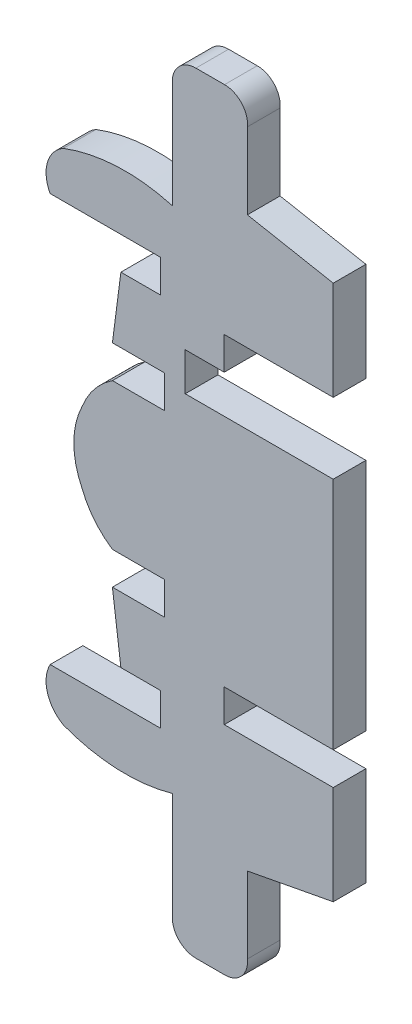
SolidWorks part; units mm, degrees
ref_plane "Front" through (0, 0, 0) normal (0, 0, 1) x (1, 0, 0)
ref_plane "Top" through (0, 0, 0) normal (0, 1, 0) x (1, 0, 0)
ref_plane "Right" through (0, 0, 0) normal (1, 0, 0) x (0, 0, -1)
sketch "Sketch1" plane through (0, 0, 0) normal (0, 0, 1) x (1, 0, 0)
  line L0 (796.0674, -94.7906) -> (796.0674, -97.7906)
  line L1 (801.5316, -91.996) -> (797.955, -91.996)
  line L2 (791.2726, -94.7906) -> (796.0674, -94.7906)
  line L3 (787.7336, -104.496) -> (811.5316, -104.496) construction
  line L4 (811.5316, -88.996) -> (811.5316, -79.92)
  line L5 (796.7638, -71.3014) -> (796.7638, -81.1469)
  line L6 (791.2726, -114.2013) -> (792.0513, -120.2055)
  line L7 (803.6575, -130.5631) -> (811.5316, -129.0719)
  line L8 (803.6575, -130.5631) -> (803.6575, -137.5522)
  line L9 (798.9334, -139.86) -> (801.5592, -139.86)
  line L10 (785.561, -123.2055) -> (795.6687, -123.2055)
  line L11 (792.0513, -120.2055) -> (795.6687, -120.2055)
  line L12 (795.6687, -120.2055) -> (795.6687, -123.2055)
  line L13 (801.5316, -88.996) -> (811.5316, -88.996)
  line L14 (797.955, -91.996) -> (797.955, -94.996)
  line L15 (796.0674, -97.7906) -> (791.2726, -97.7906)
  line L17 (796.0674, -111.2013) -> (791.2726, -111.2013)
  line L18 (801.5316, -91.996) -> (801.5316, -88.996)
  line L19 (796.7638, -137.6905) -> (796.7638, -127.8451)
  line L20 (811.5316, -119.996) -> (811.5316, -129.0719)
  line L21 (791.2726, -114.2013) -> (796.0674, -114.2013)
  line L22 (811.5316, -95.496) -> (811.5316, -116.996)
  line L23 (811.5316, -116.996) -> (801.5316, -116.996)
  line L24 (795.6687, -88.7864) -> (795.6687, -85.7864)
  line L25 (792.0513, -88.7864) -> (795.6687, -88.7864)
  line L26 (785.561, -85.7864) -> (795.6687, -85.7864)
  line L27 (798.9334, -69.1319) -> (801.5592, -69.1319)
  line L28 (803.6575, -78.4289) -> (803.6575, -71.4397)
  line L29 (796.0674, -114.2013) -> (796.0674, -111.2013)
  line L30 (803.6575, -78.4289) -> (811.5316, -79.92)
  line L31 (791.2726, -94.7906) -> (792.0513, -88.7864)
  line L32 (801.5316, -116.996) -> (801.5316, -119.996)
  line L33 (801.5316, -119.996) -> (811.5316, -119.996)
  line L34 (797.955, -94.996) -> (797.955, -95.496)
  line L35 (797.955, -95.496) -> (811.5316, -95.496)
  arc A0 (801.5592, -139.86) -> (803.6575, -137.5522) centre (801.5697, -137.7618) ccw
  arc A1 (796.7638, -137.6905) -> (798.9334, -139.86) centre (798.9334, -137.6905) ccw
  arc A2 (788.4711, -101.2864) -> (791.2726, -97.7906) centre (795.3367, -103.9179) cw
  arc A3 (785.561, -123.2055) -> (786.769, -127.402) centre (788.3063, -124.6874) ccw
  arc A4 (786.769, -127.402) -> (796.7638, -127.8451) centre (792.436, -112.5206) ccw
  arc A5 (786.769, -81.59) -> (796.7638, -81.1469) centre (792.436, -96.4714) cw
  arc A6 (785.561, -85.7864) -> (786.769, -81.59) centre (788.3063, -84.3046) cw
  arc A7 (796.7638, -71.3014) -> (798.9334, -69.1319) centre (798.9334, -71.3014) cw
  arc A8 (801.5592, -69.1319) -> (803.6575, -71.4397) centre (801.5697, -71.2302) cw
  arc A9 (788.4711, -101.2864) -> (788.4711, -107.7055) centre (795.0862, -104.496) ccw
  arc A10 (788.4711, -107.7055) -> (791.2726, -111.2013) centre (795.3367, -105.0741) ccw
  dimension "D2" = 3
  dimension "D3" = 10
  dimension "D4" = 0.5
extrude "Base-Extrude" add sketch "Sketch1" along normal blind 3
